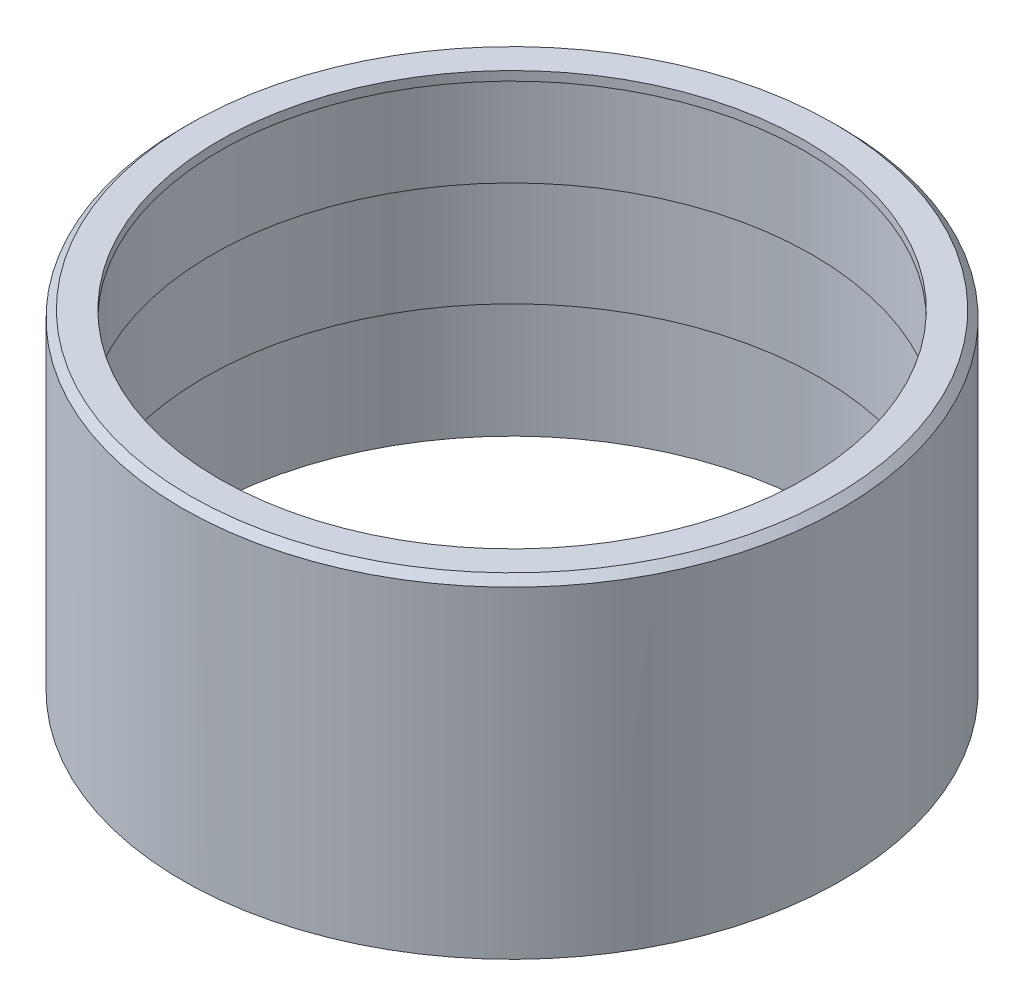
SolidWorks part; units mm, degrees
material "6061 Alloy"
ref_plane "Front Plane" through (0, 0, 0) normal (0, 0, 1) x (1, 0, 0)
ref_plane "Top Plane" through (0, 0, 0) normal (0, 1, 0) x (1, 0, 0)
ref_plane "Right Plane" through (0, 0, 0) normal (1, 0, 0) x (0, 0, -1)
sketch "Sketch1" plane through (0, 0, 0) normal (0, 0, 1) x (1, 0, 0)
  line L0 (20.32, 22.225) -> (20.32, 22.86)
  line L1 (22.86, 22.86) -> (22.86, 0)
  line L2 (21.336, 14.224) -> (22.86, 14.224) construction
  line L3 (0, -7.7413) -> (0, 33.0894) construction
  line L8 (22.86, 22.86) -> (20.32, 22.86)
  line L15 (21.59, 5.588) -> (21.59, 2.413)
  line L16 (22.225, 0) -> (22.86, 0)
  line L17 (22.225, 2.413) -> (22.225, 0)
  line L18 (21.59, 2.413) -> (22.225, 2.413)
  line L19 (20.828, 21.59) -> (20.828, 15.748)
  line L20 (21.59, 8.128) -> (21.59, 5.588)
  line L21 (21.336, 8.128) -> (21.59, 8.128)
  line L22 (21.336, 15.748) -> (21.336, 8.128)
  line L23 (20.828, 15.748) -> (21.336, 15.748)
  line L24 (20.828, 22.225) -> (20.828, 21.59)
  line L25 (20.32, 22.225) -> (20.828, 22.225)
  dimension "D1" = 0.635
  dimension "D2" = 0.508
  dimension "D3" = 0.635
  dimension "D4" = 5.842
  dimension "D5" = 7.62
  dimension "D6" = 2.54
  dimension "D7" = 3.175
  dimension "D8" = 2.413
  dimension "D9" = 0.635
  dimension "D10" = 0.635
  dimension "D11" = 0.254
  dimension "D12" = 0.508
  dimension "D13" = 21.336
  dimension "D14" = 22.86
  dimension "D15" = 22.86
  dimension "D16" = 20.828
  dimension "D17" = 20.32
  dimension "D18" = 1.524
  dimension "D19" = 8.636
revolve "Revolve1" add sketch "Sketch1" angle 360 about L3
chamfer "Chamfer1" distance 0.508 angle 45 1 edges at (0, 22.86, -22.86)
chamfer "Chamfer2" distance 0.254 angle 45 1 edges at (0, 0, -22.225)
sketch "Sketch2" plane through (0, 0, 0) normal (0, -1, 0) x (1, 0, 0)
  circle A0 centre (0, 0) radius 22.86
  circle A1 centre (0, 0) radius 21.59
extrude "Boss-Extrude1" add sketch "Sketch2" against normal up to next
